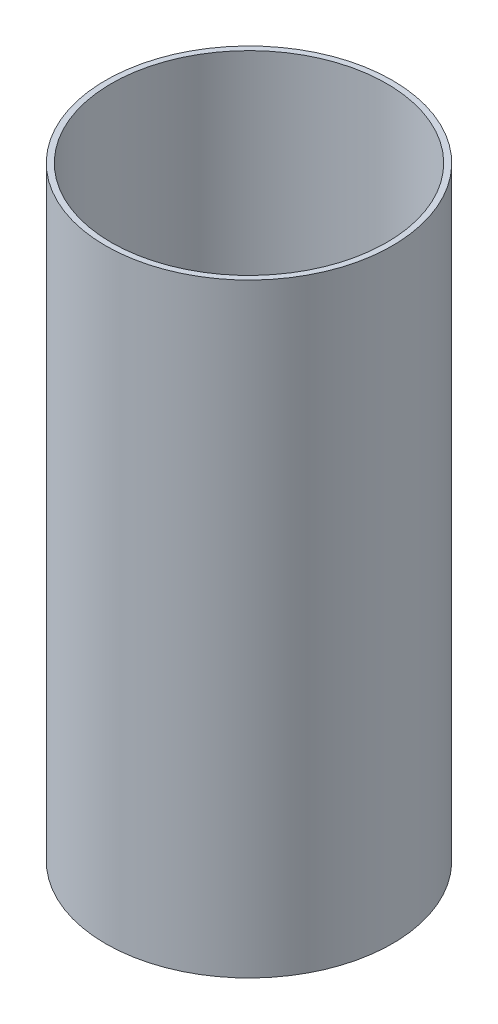
SolidWorks part; units mm, degrees
ref_plane "Front Plane" through (0, 0, 0) normal (0, 0, 1) x (1, 0, 0)
ref_plane "Top Plane" through (0, 0, 0) normal (0, 1, 0) x (1, 0, 0)
ref_plane "Right Plane" through (0, 0, 0) normal (1, 0, 0) x (0, 0, -1)
sketch "Sketch1" plane through (0, 0, 0) normal (0, 1, 0) x (1, 0, 0)
  circle A0 centre (0, 0) radius 36.45
  circle A1 centre (0, 0) radius 37.95
  dimension "D1" = 72.9
  dimension "D2" = 1.5
extrude "Boss-Extrude1" add sketch "Sketch1" along normal blind 160
